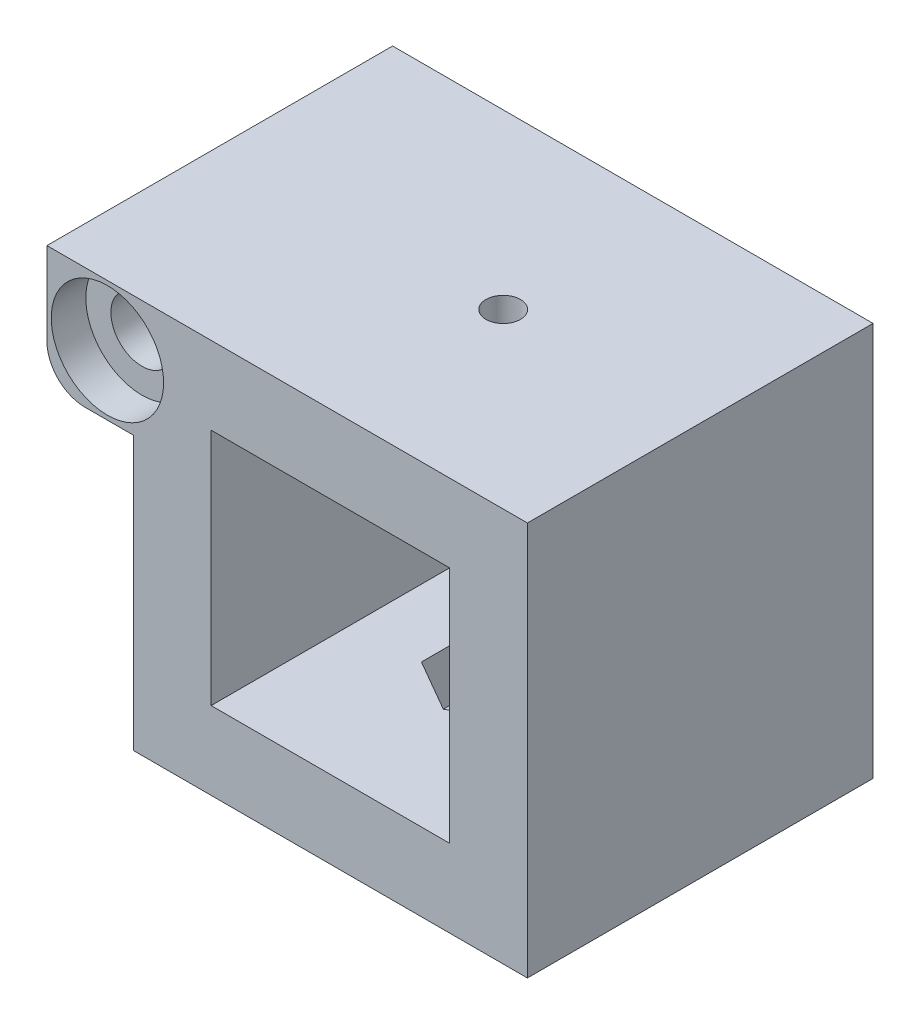
SolidWorks part; units mm, degrees
ref_plane "Alzado" through (0, 0, 0) normal (0, 0, 1) x (1, 0, 0)
ref_plane "Planta" through (0, 0, 0) normal (0, 1, 0) x (1, 0, 0)
ref_plane "Vista lateral" through (0, 0, 0) normal (1, 0, 0) x (0, 0, -1)
sketch "Croquis1" plane through (0, 0, 0) normal (0, 0, 1) x (1, 0, 0)
  line L0 (-11.4, -11.4) -> (-11.4, 11.4)
  line L1 (-6.9, -6.9) -> (6.9, -6.9)
  line L2 (-6.9, -6.9) -> (-6.9, 6.9)
  line L3 (-6.9, 6.9) -> (6.9, 6.9)
  line L4 (6.9, -6.9) -> (6.9, 6.9)
  line L5 (-6.9, -6.9) -> (6.9, 6.9) construction
  line L6 (-6.9, 6.9) -> (6.9, -6.9) construction
  line L7 (-11.4, 11.4) -> (11.4, 11.4)
  line L8 (11.4, -11.4) -> (11.4, 11.4)
  line L9 (-11.4, -11.4) -> (11.4, -11.4)
  point P0 (0, 0)
  dimension "D1" = 13.8
  dimension "D2" = 13.8
  dimension "D3" = 4.5
extrude "Saliente-Extruir1" add sketch "Croquis1" along normal mid plane 20
sketch "Croquis2" plane through (0, -6.9, 0) normal (0, 1, 0) x (1, 0, 0)
  line L1 (3, -1.7321) -> (3, 1.7321)
  line L2 (3, 1.7321) -> (0, 3.4641)
  line L3 (0, 3.4641) -> (-3, 1.7321)
  line L4 (-3, 1.7321) -> (-3, -1.7321)
  line L5 (-3, -1.7321) -> (0, -3.4641)
  line L6 (0, -3.4641) -> (3, -1.7321)
  circle A0 centre (0, 0) radius 3 construction
  dimension "D1" = 6
extrude "Cortar-Extruir1" cut sketch "Croquis2" against normal blind 3
sketch "Croquis3" plane through (0, -9.9, 0) normal (0, 1, 0) x (1, 0, 0)
  circle A0 centre (0, 0) radius 1.75
  dimension "D1" = 3.5
extrude "Cortar-Extruir2" cut sketch "Croquis3" against normal blind 3
sketch "Croquis4" plane through (0, 0, -10) normal (0, 0, -1) x (-1, 0, 0)
  line L0 (12.9, 11.4) -> (12.9, 4.4) construction
  line L1 (11.4, 11.4) -> (16.4, 11.4)
  line L2 (11.4, 11.4) -> (11.4, 4.4)
  line L3 (11.4, 4.4) -> (16.4, 4.4)
  line L4 (-11.4, -11.4) -> (11.4, -11.4)
  line L5 (11.4, -11.4) -> (11.4, 11.4)
  line L6 (11.4, 11.4) -> (-11.4, 11.4)
  line L7 (-11.4, 11.4) -> (-11.4, -11.4)
  line L8 (-11.4, -11.4) -> (11.4, -11.4)
  line L9 (11.4, -11.4) -> (11.4, 11.4)
  line L10 (11.4, 11.4) -> (-11.4, 11.4)
  line L11 (-11.4, 11.4) -> (-11.4, -11.4)
  line L12 (16.4, 11.4) -> (16.4, 4.4)
  circle A0 centre (12.9, 7.9) radius 1.6
  line M12 (11.4, -11.4) -> (11.4, 11.4)
  dimension "D2" = 3.2
  dimension "D3" = 5
  dimension "D4" = 1.5
  dimension "D5" = 7
  dimension "D1" = 0
extrude "Saliente-Extruir3" add sketch "Croquis4" against normal through all contours L1 L0 A0 L3 L12 | L0 A0 L3 M12 | L0 L1 A0 M12
sketch "Croquis8" plane through (0, 0, -10) normal (0, 0, -1) x (-1, 0, 0)
  circle A0 centre (12.9, 7.9) radius 1.75
extrude "Cortar-Extruir3" cut sketch "Croquis8" against normal blind 4
hole_wizard "Refrentado para tornillo con cabeza plana de M31" positions "Croquis3D2" profile "Croquis9" counterbore size "M3" standard "ISO" end condition through all
sketch3d "Croquis3D2"
  line L0 (-12.9, 7.9, 10) -> (-12.9, 7.9, -6) construction
  point P0 (-12.9, 7.9, 10)
sketch "Croquis9" plane through (-12.9, 7.9, 10) normal (1, 0, 0) x (0, -1, 0)
  line L0 (0, 0) -> (0, 20)
  line L1 (0, 20) -> (1.8, 20)
  line L3 (1.8, 20) -> (1.8, 2)
  line L4 (1.8, 2) -> (3.25, 2)
  line L5 (3.25, 2) -> (3.25, 0)
  line L7 (3.25, 0) -> (0, 0)
  line L11 (0, -6.35) -> (0, 107.95) construction
  dimension "Diámetro de taladro hasta el siguiente" = 3.6
  dimension "Profundidad de taladro hasta el siguiente" = 20
  dimension "Diámetro de refrentado" = 6.5
  dimension "Profundidad de refrentado" = 2
sketch "Croquis11" plane through (0, 0, 10) normal (0, 0, 1) x (1, 0, 0)
  circle A1 centre (-12.9, 7.9) radius 3.25
  circle A2 centre (-12.9, 7.9) radius 3.25 construction
fillet "Redondeo1" radius 2.2 1 edges at (-16.4, 4.4, 0)
sketch "Croquis12" plane through (0, 11.4, 0) normal (0, 1, 0) x (1, 0, 0)
  circle A0 centre (0, 0) radius 1
  dimension "D1" = 2
extrude "Cortar-Extruir5" cut sketch "Croquis12" against normal blind 10
